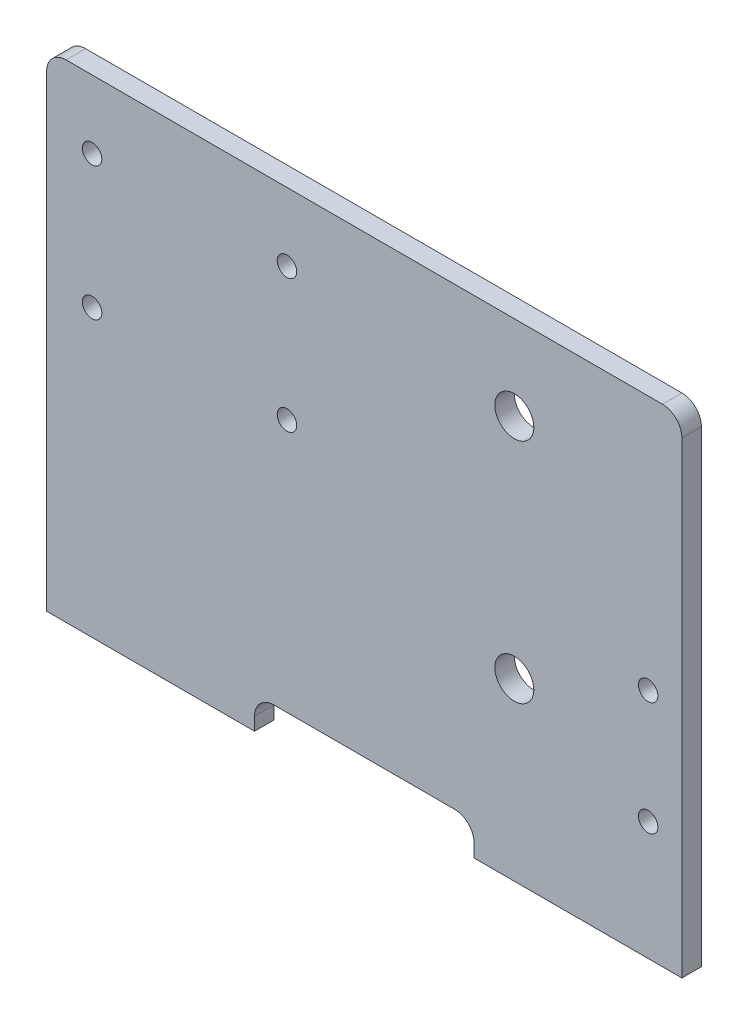
SolidWorks part; units mm, degrees
material "MDF"
ref_plane "Alzado" through (0, 0, 0) normal (0, 0, 1) x (1, 0, 0)
ref_plane "Planta" through (0, 0, 0) normal (0, 1, 0) x (1, 0, 0)
ref_plane "Vista lateral" through (0, 0, 0) normal (1, 0, 0) x (0, 0, -1)
sketch "Croquis1" plane through (0, 0, 0) normal (0, 0, 1) x (1, 0, 0)
  line L1 (-48.9, 37.5) -> (48.9, 37.5)
  line L2 (-48.9, 37.5) -> (-48.9, -37.5)
  line L3 (-48.9, -37.5) -> (48.9, -37.5)
  line L4 (48.9, 37.5) -> (48.9, -37.5)
  line L5 (-48.9, 37.5) -> (48.9, -37.5) construction
  line L6 (-48.9, -37.5) -> (48.9, 37.5) construction
  circle A0 centre (-41.9, 27) radius 1.5
  circle A3 centre (-11.9, 27) radius 1.5
  circle A4 centre (-11.9, 6.5) radius 1.5
  circle A5 centre (-41.9, 6.5) radius 1.5
  circle A6 centre (23.1, -10.5) radius 3
  circle A7 centre (23.1, 24.5) radius 3
  circle A11 centre (43.7, -1.75) radius 1.5
  circle A12 centre (43.7, -19.25) radius 1.5
  point P0 (0, 0)
  dimension "D3" = 3
  dimension "D10" = 6
  dimension "D13" = 6
  dimension "D16" = 3
  dimension "D1" = 75
  dimension "D2" = 97.8
  dimension "D4" = 10.5
  dimension "D5" = 7
  dimension "D8" = 37
  dimension "D9" = 31
  dimension "D11" = 25.8
  dimension "D12" = 27
  dimension "D14" = 13
  dimension "D15" = 25.8
  dimension "D17" = 5.2
  dimension "D18" = 35.75
  dimension "D19" = 17.5
  dimension "D6" = 2
  dimension "D7" = 2
extrude "Saliente-Extruir1" add sketch "Croquis1" along normal mid plane 3
sketch "Croquis2" plane through (0, 0, 1.5) normal (0, 0, 1) x (1, 0, 0)
  line L0 (-48.9, 37.5) -> (-48.9, -37.5) construction
  line L1 (16.9, -37.5) -> (-16.9, -37.5)
  line L2 (16.9, -37.5) -> (16.9, -32.5)
  line L3 (16.9, -32.5) -> (-16.9, -32.5)
  line L4 (-16.9, -37.5) -> (-16.9, -32.5)
  line L5 (-48.9, -37.5) -> (48.9, -37.5) construction
  line L6 (48.9, -37.5) -> (48.9, 37.5) construction
  dimension "D1" = 5
  dimension "D2" = 32
  dimension "D3" = 32
extrude "Cortar-Extruir1" cut sketch "Croquis2" against normal through all
fillet "Redondeo1" radius 3 4 edges at (-48.9, 37.5, 0) (48.9, 37.5, 0) (16.9, -32.5, 0) (-16.9, -32.5, 0)
